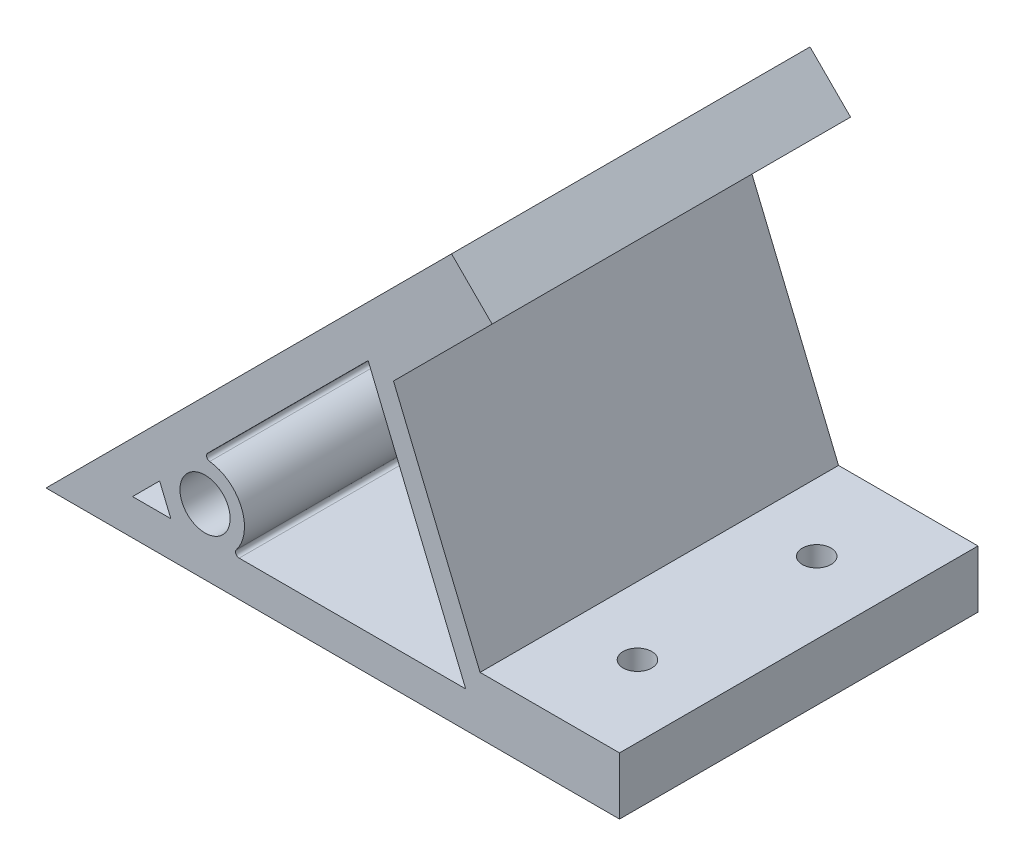
SolidWorks part; units mm, degrees
ref_plane "前视基准面" through (0, 0, 0) normal (0, 0, 1) x (1, 0, 0)
ref_plane "上视基准面" through (0, 0, 0) normal (0, 1, 0) x (1, 0, 0)
ref_plane "右视基准面" through (0, 0, 0) normal (1, 0, 0) x (0, 0, -1)
sketch "草图1" plane through (0, 0, 0) normal (0, 0, 1) x (1, 0, 0)
  line L0 (0, 0) -> (56.5685, 56.5685)
  line L1 (0, 0) -> (80, 0)
  line L2 (12.0711, 5) -> (15.8477, 8.7766)
  line L3 (12.0711, 5) -> (17.412, 5)
  line L4 (15.8477, 8.7766) -> (17.412, 5)
  line L5 (0, 0) -> (16.6385, 6.8674) construction
  line L6 (22.5392, 15.4681) -> (44.9316, 37.8605)
  line L7 (26.9418, 5) -> (58.5429, 5)
  line L8 (12.0711, 5) -> (60.1041, 53.033) construction
  line L9 (58.5429, 5) -> (44.9316, 37.8605)
  line L10 (12.0711, 5) -> (80, 5) construction
  line L11 (60.5474, 8) -> (48.4704, 37.1566)
  line L12 (61.3145, 6.1481) -> (47.7033, 39.0086) construction
  line L13 (62.2254, 50.9117) -> (56.5685, 56.5685)
  line L14 (80, 0) -> (80, 8)
  line L15 (60.5474, 8) -> (80, 8)
  line L16 (50.7665, 39.4527) -> (62.2254, 50.9117) construction
  line L17 (48.4704, 37.1566) -> (62.2254, 50.9117)
  line L18 (63.7946, 8) -> (50.7665, 39.4527) construction
  line L19 (63.7946, 8) -> (80, 8) construction
  line L20 (61.7901, 5) -> (80, 5) construction
  line L21 (47.2277, 40.1566) -> (60.1041, 53.033) construction
  line L23 (61.7901, 5) -> (47.2277, 40.1566) construction
  circle A0 centre (22.1847, 9.1565) radius 3.5
  arc A1 (26.5454, 5.8047) -> (22.8337, 14.618) centre (22.1847, 9.1565) ccw
  arc A2 (26.9418, 5) -> (26.5454, 5.8047) centre (26.9418, 5.5) cw
  circle A3 centre (22.1847, 9.1565) radius 5.5 construction
  arc A4 (22.5392, 15.4681) -> (22.8337, 14.618) centre (22.8927, 15.1145) ccw
  point P15 (27.6847, 9.1565)
  point P20 (25.7866, 5)
  point P23 (21.7067, 14.6357)
  dimension "D7" = 7
  dimension "D8" = 2
  dimension "D9" = 0.5
  dimension "D10" = 56
  dimension "D1" = 45
  dimension "D2" = 80
  dimension "D4" = 67.5
  dimension "D5" = 18
  dimension "D6" = 6
  dimension "D3" = 5
  dimension "D11" = 3
  dimension "D12" = 3
extrude "凸台-拉伸1" add sketch "草图1" along normal mid plane 50
sketch "草图2" plane through (0, 0, 0) normal (-0.7071, 0.7071, 0) x (0, 0, 1)
  line L0 (0, 80) -> (0, 53.9096) construction
  line L1 (25, 80) -> (-25, 80) construction
  circle A0 centre (-12.5, 70) radius 2
  circle A1 centre (12.5, 70) radius 2
  dimension "D1" = 25
  dimension "D3" = 4
  dimension "D2" = 10
extrude "切除-拉伸1" cut sketch "草图2" against normal blind 20
sketch "草图3" plane through (0, 0, 0) normal (0, -1, 0) x (1, 0, 0)
  line L0 (80, 0) -> (48.7562, 0) construction
  line L1 (80, 25) -> (80, -25) construction
  circle A0 centre (70, 12.5) radius 2
  circle A1 centre (70, -12.5) radius 2
  dimension "D1" = 25
  dimension "D2" = 10
  dimension "D3" = 4
extrude "切除-拉伸2" cut sketch "草图3" against normal blind 20
